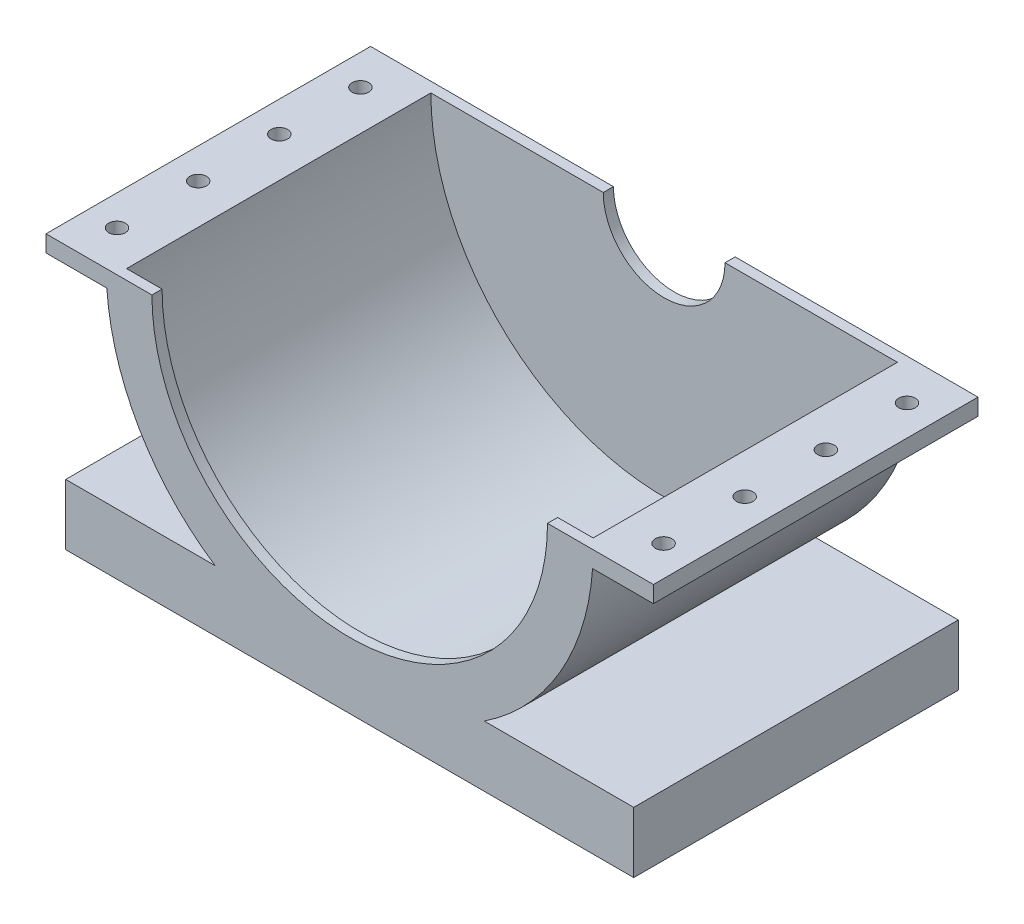
SolidWorks part; units mm, degrees
ref_plane "Front Plane" through (0, 0, 0) normal (0, 0, 1) x (1, 0, 0)
ref_plane "Top Plane" through (0, 0, 0) normal (0, 1, 0) x (1, 0, 0)
ref_plane "Right Plane" through (0, 0, 0) normal (1, 0, 0) x (0, 0, -1)
sketch "Sketch1" plane through (0, 0, 0) normal (0, 0, 1) x (1, 0, 0)
  line L0 (-7, 0) -> (7, 0)
  line L1 (7, 0) -> (7, 1.5)
  line L2 (7, 1.5) -> (3.3166, 1.5)
  line L3 (-4.875, 6.5) -> (4.875, 6.5)
  line L5 (4.875, 6.5) -> (7.486, 6.5)
  line L6 (7.486, 6.5) -> (7.486, 6.09)
  line L7 (7.486, 6.09) -> (5.986, 6.09)
  line L9 (-7, 1.5) -> (-3.3166, 1.5)
  line L10 (-7, 0) -> (-7, 1.5)
  line L11 (-4.875, 6.5) -> (-7.486, 6.5)
  line L12 (-7.486, 6.5) -> (-7.486, 6.09)
  line L13 (-7.486, 6.09) -> (-5.986, 6.09)
  arc A2 (5.986, 6.09) -> (3.3166, 1.5) centre (0, 6.5) cw
  arc A3 (-5.986, 6.09) -> (-3.3166, 1.5) centre (0, 6.5) ccw
  point P15 (0, 0)
  dimension "D1" = 6
  dimension "D2" = 3.3166
  dimension "D3" = 6
  dimension "D4" = 1.5
  dimension "D5" = 5
  dimension "D6" = 0.41
  dimension "D7" = 1.5
  dimension "D8" = 7
  dimension "D9" = 4.875
  dimension "D10" = 5.986
extrude "Boss-Extrude1" add sketch "Sketch1" along normal blind 8
ref_plane "Plane1" through (0, 0, 4) normal (0, 0, 1) x (1, 0, 0)
sketch "Sketch3" plane through (0, 0, 4) normal (0, 0, 1) x (1, 0, 0)
  line L0 (7.486, 6.5) -> (-7.486, 6.5) construction
  line L1 (5.75, 6.5) -> (-5.75, 6.5)
  arc A0 (-5.75, 6.5) -> (5.75, 6.5) centre (0, 6.5) ccw
  dimension "D1" = 11.5
extrude "Cut-Extrude1" cut sketch "Sketch3" against normal mid plane 7.5
sketch "Sketch4" plane through (0, 0, 8) normal (0, 0, 1) x (1, 0, 0)
  line L0 (7.486, 6.5) -> (-7.486, 6.5) construction
  line L1 (-4.875, 6.5) -> (4.875, 6.5)
  arc A0 (-4.875, 6.5) -> (4.875, 6.5) centre (0, 6.5) ccw
  dimension "D1" = 9.75
sketch "Sketch5" plane through (0, 0, 8) normal (0, 0, 1) x (1, 0, 0)
  line L0 (-5.75, 6.5) -> (5.75, 6.5)
extrude "Cut-Extrude2" cut sketch "Sketch4" against normal mid plane 7.5
sketch "Sketch6" plane through (0, 0, 0.25) normal (0, 0, 1) x (1, 0, 0)
  line L0 (5.75, 6.5) -> (-5.75, 6.5) construction
  line L1 (-1.5, 6.5) -> (1.5, 6.5)
  arc A0 (-1.5, 6.5) -> (1.5, 6.5) centre (0, 6.5) ccw
  dimension "D1" = 1.5
extrude "Cut-Extrude3" cut sketch "Sketch6" against normal mid plane 7.5
sketch "Sketch7" plane through (0, 6.5, 0) normal (0, 1, 0) x (1, 0, 0)
  line L0 (7.486, -8) -> (4.875, -8) construction
  line L1 (7.486, 0) -> (1.5, 0) construction
  line L2 (7.486, -8) -> (7.486, 0) construction
  circle A0 centre (6.736, -1) radius 0.205
  circle A1 centre (6.736, -3) radius 0.205
  circle A2 centre (6.736, -5) radius 0.205
  circle A3 centre (6.736, -7) radius 0.205
  point P8 (0, 0)
  point P11 (0, 0)
  point P12 (0, 0)
  point P13 (0, 0)
  dimension "D1" = 0.41
  dimension "D2" = 1
  dimension "D3" = 1
  dimension "D4" = 2
  dimension "D5" = 2
  dimension "D6" = 0.75
extrude "Cut-Extrude5" cut sketch "Sketch7" against normal blind 2 contours A3 | A2 | A1 | A0
mirror "Mirror1" about plane through (0, 0, 0) normal (1, 0, 0) of "Cut-Extrude5"
